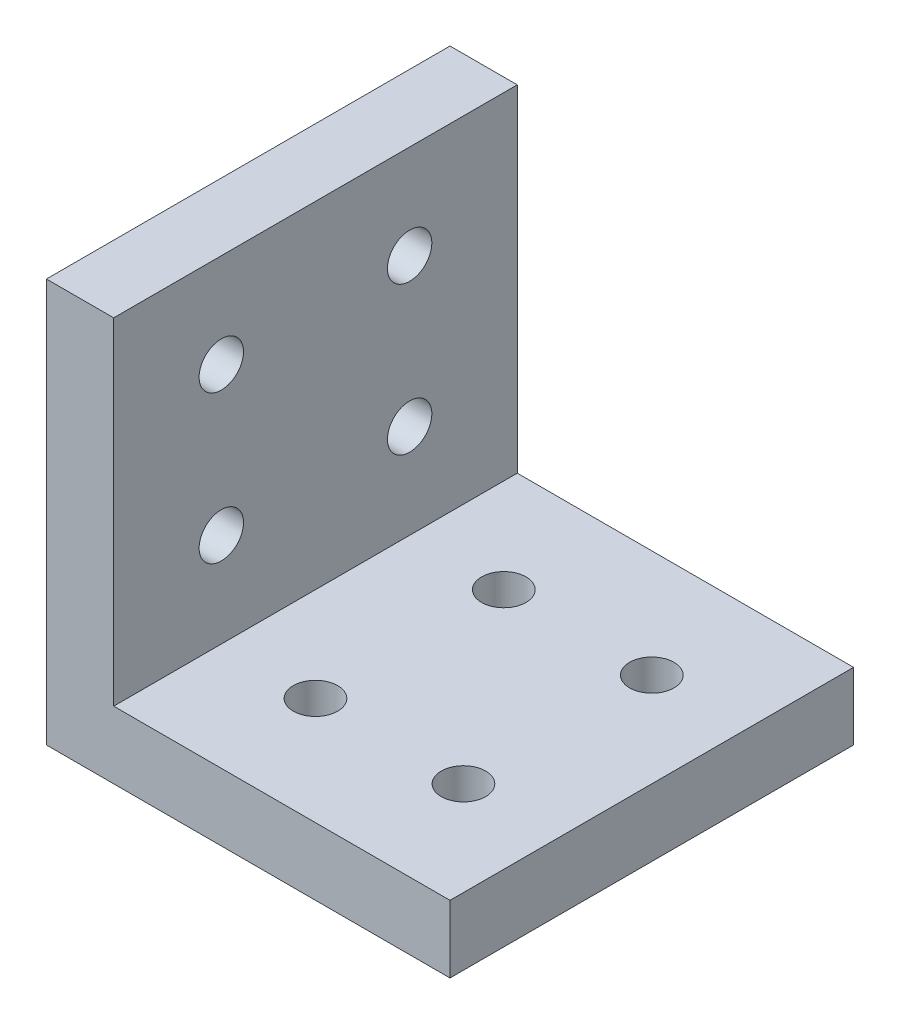
SolidWorks part; units mm, degrees
ref_plane "前视基准面" through (0, 0, 0) normal (0, 0, 1) x (1, 0, 0)
ref_plane "上视基准面" through (0, 0, 0) normal (0, 1, 0) x (1, 0, 0)
ref_plane "右视基准面" through (0, 0, 0) normal (1, 0, 0) x (0, 0, -1)
other "Configuration Table"
sketch "草图1" plane through (0, 0, 0) normal (0, 0, 1) x (1, 0, 0)
  line L0 (0, 30) -> (0, 0)
  line L1 (0, 0) -> (30, 0)
  line L2 (30, 0) -> (30, 5)
  line L3 (30, 5) -> (5, 5)
  line L4 (5, 5) -> (5, 30)
  line L5 (5, 30) -> (0, 30)
  dimension "D1" = 30
  dimension "D2" = 30
  dimension "D3" = 5
  dimension "D4" = 5
extrude "凸台-拉伸1" add sketch "草图1" along normal blind 30
sketch "草图2" plane through (0, 5, 0) normal (0, 1, 0) x (1, 0, 0)
  line L0 (23, -8) -> (23, -22) construction
  line L1 (30, 0) -> (5, 0) construction
  line L2 (30, -30) -> (30, 0) construction
  line L3 (23, -8) -> (12, -8) construction
  line L4 (12, -8) -> (12, -22) construction
  line L5 (12, -22) -> (23, -22) construction
  circle A0 centre (23, -8) radius 1.65
  circle A1 centre (23, -22) radius 1.65
  circle A2 centre (12, -8) radius 1.65
  circle A3 centre (12, -22) radius 1.65
  dimension "D5" = 3.3
  dimension "D1" = 14
  dimension "D2" = 8
  dimension "D3" = 7
  dimension "D4" = 11
extrude "切除-拉伸1" cut sketch "草图2" against normal blind 40
sketch "草图3" plane through (5, 0, 0) normal (1, 0, 0) x (0, 0, -1)
  line L0 (-30, 30) -> (0, 30) construction
  line L1 (-22, 12) -> (-8, 12) construction
  line L2 (-22, 12) -> (-22, 23) construction
  line L3 (-22, 23) -> (-8, 23) construction
  line L4 (-8, 12) -> (-8, 23) construction
  line L5 (0, 5) -> (0, 30) construction
  circle A0 centre (-22, 23) radius 1.65
  circle A1 centre (-22, 12) radius 1.65
  circle A2 centre (-8, 23) radius 1.65
  circle A3 centre (-8, 12) radius 1.65
  dimension "D5" = 3.3
  dimension "D1" = 14
  dimension "D2" = 7
  dimension "D3" = 11
  dimension "D4" = 8
extrude "切除-拉伸2" cut sketch "草图3" against normal blind 40
